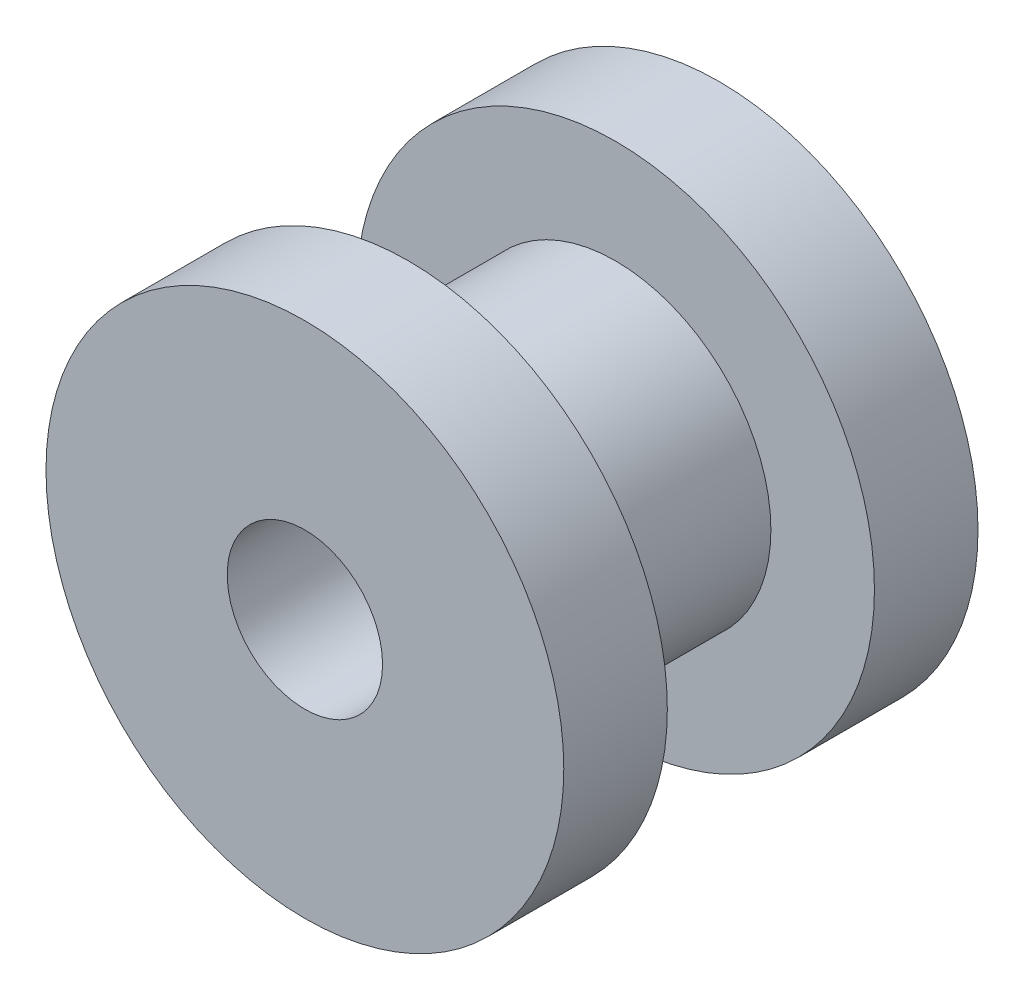
SolidWorks part; units mm, degrees
material "PE High Density"
ref_plane "Front Plane" through (0, 0, 0) normal (0, 0, 1) x (1, 0, 0)
ref_plane "Top Plane" through (0, 0, 0) normal (0, 1, 0) x (1, 0, 0)
ref_plane "Right Plane" through (0, 0, 0) normal (1, 0, 0) x (0, 0, -1)
sketch "Sketch1" plane through (0, 0, 0) normal (0, 0, 1) x (1, 0, 0)
  circle A0 centre (0, 0) radius 1.5
  dimension "D1" = 3
extrude "Boss-Extrude1" add sketch "Sketch1" along normal mid plane 2
sketch "Sketch2" plane through (0, 0, 1) normal (0, 0, 1) x (1, 0, 0)
  circle A0 centre (0, 0) radius 2.5
  dimension "D1" = 5
extrude "Boss-Extrude2" add sketch "Sketch2" along normal blind 1
mirror "Mirror1" about plane through (0, 0, 0) normal (0, 0, 1) of "Boss-Extrude2"
sketch "Sketch3" plane through (0, 0, 2) normal (0, 0, 1) x (1, 0, 0)
  circle A0 centre (0, 0) radius 0.75
  dimension "D1" = 1.5
extrude "Cut-Extrude1" cut sketch "Sketch3" against normal through all
